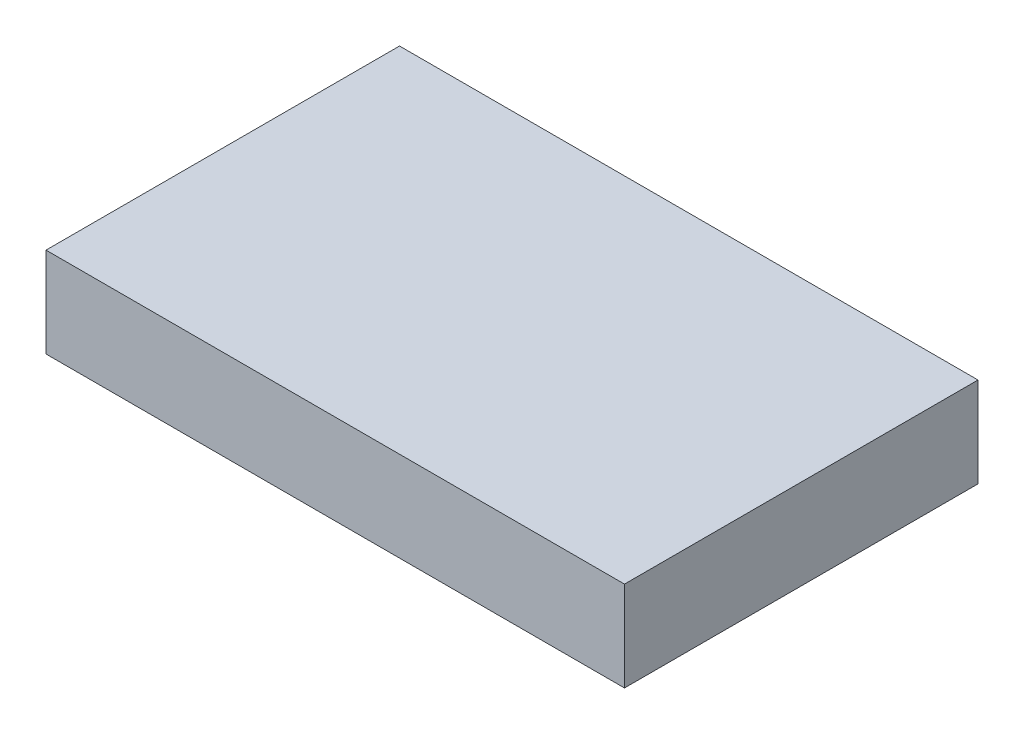
SolidWorks part; units mm, degrees
ref_plane "Plano frontal" through (0, 0, 0) normal (0, 0, 1) x (1, 0, 0)
ref_plane "Plano superior" through (0, 0, 0) normal (0, 1, 0) x (1, 0, 0)
ref_plane "Plano direito" through (0, 0, 0) normal (1, 0, 0) x (0, 0, -1)
sketch "Esboço1" plane through (0, 0, 0) normal (0, 0, 1) x (1, 0, 0)
  line L0 (-45, 0) -> (45, 0)
  line L1 (-45, 0) -> (-45, 14)
  line L2 (-45, 14) -> (45, 14)
  line L3 (45, 14) -> (45, 0)
  point P4 (0, 0)
  dimension "D1" = 90
  dimension "D2" = 14
extrude "Ressalto-extrusão1" add sketch "Esboço1" along normal blind 55
